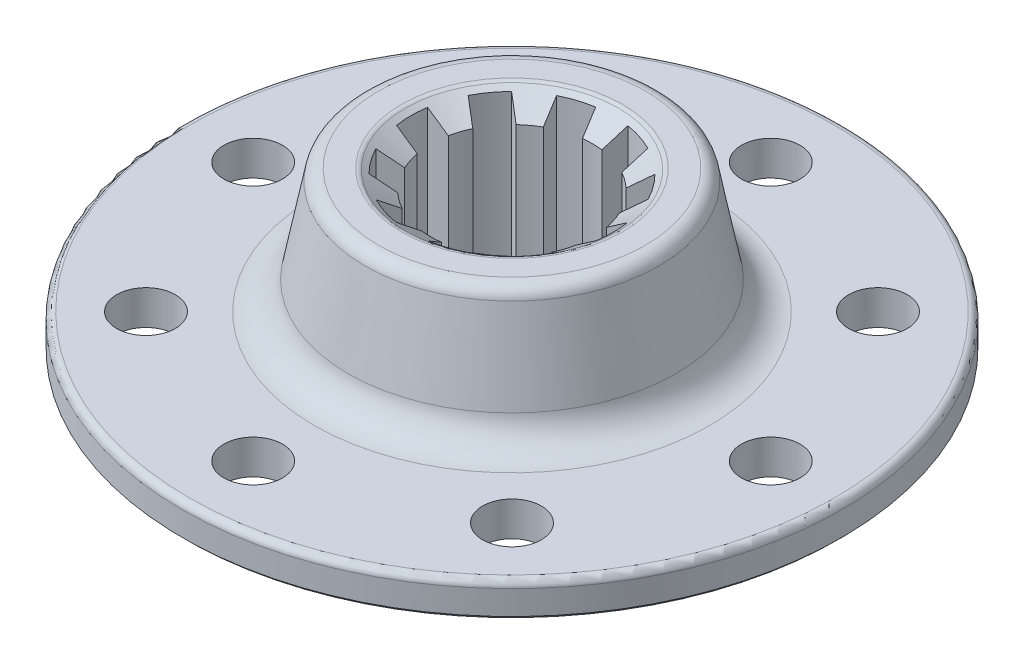
SolidWorks part; units mm, degrees
ref_plane "Plano frontal" through (0, 0, 0) normal (0, 0, 1) x (1, 0, 0)
ref_plane "Plano superior" through (0, 0, 0) normal (0, 1, 0) x (1, 0, 0)
ref_plane "Plano direito" through (0, 0, 0) normal (1, 0, 0) x (0, 0, -1)
sketch "Esboço1" plane through (0, 0, 0) normal (0, 0, 1) x (1, 0, 0)
  line L0 (0, -45.6966) -> (0, 49.4495) construction
  line L1 (11.7, 16.6829) -> (11.7, -10.8171)
  line L2 (11.7, -10.8171) -> (19.25, -10.8171)
  line L3 (19.25, -10.8171) -> (22.25, -7.8171)
  line L4 (22.25, -7.8171) -> (25.9, -7.8171)
  line L5 (27.5, -6.3171) -> (27, -5.8171)
  line L6 (27, -5.8171) -> (25.9, -5.8171)
  line L7 (27.5, -6.3171) -> (47.75, -6.3171)
  line L8 (47.75, -6.3171) -> (47.75, -1.3171)
  line L9 (21, 16.6829) -> (24.4988, -1.3171)
  line L10 (24.4988, -1.3171) -> (47.75, -1.3171)
  line L11 (21, 16.6829) -> (11.7, 16.6829)
  line L12 (25.9, -5.8171) -> (25.9, -7.8171)
  dimension "D1" = 11.7
  dimension "D2" = 21
  dimension "D3" = 11
  dimension "D4" = 3
  dimension "D5" = 19.25
  dimension "D6" = 22.25
  dimension "D7" = 25.9
  dimension "D8" = 27.5
  dimension "D9" = 0.5
  dimension "D10" = 47.75
  dimension "D11" = 4.5
  dimension "D12" = 5
  dimension "D13" = 18
revolve "Revolução1" add sketch "Esboço1" angle 360 about L0
fillet "Filete1" radius 5 1 edges at (0, -1.3171, -24.4988)
chamfer "Chanfro1" distance 4 angle 35 1 edges at (0, 16.6829, -11.7)
chamfer "Chanfro2" distance 3.5 angle 35 1 edges at (0, -10.8171, -11.7)
fillet "Filete2" radius 2 1 edges at (0, 16.6829, -21)
sketch "Esboço2" plane through (0, 16.6829, 0) normal (0, 1, 0) x (1, 0, 0)
  line L0 (-14.65, 0) -> (14.65, 0) construction
  line L1 (0, 11.7) -> (0, -11.7) construction
  line L2 (-9.6848, 2.25) -> (-9.6848, -2.25)
  line L3 (-6.5126, 7.5128) -> (-9.1577, 3.8723)
  line L4 (-14.4762, 2.25) -> (-9.6848, 2.25)
  line L5 (-14.4762, -2.25) -> (-9.6848, -2.25)
  line L6 (-10.389, 10.3292) -> (-6.5126, 7.5128)
  line L7 (-13.034, 6.6886) -> (-9.1577, 3.8723)
  line L8 (-0.8529, 9.906) -> (-5.1326, 8.5155)
  line L9 (-2.3335, 14.463) -> (-0.8529, 9.906)
  line L10 (-6.6133, 13.0724) -> (-5.1326, 8.5155)
  line L11 (5.1326, 8.5155) -> (0.8529, 9.906)
  line L12 (6.6133, 13.0724) -> (5.1326, 8.5155)
  line L13 (2.3335, 14.463) -> (0.8529, 9.906)
  line L14 (9.1577, 3.8723) -> (6.5126, 7.5128)
  line L15 (13.034, 6.6886) -> (9.1577, 3.8723)
  line L16 (10.389, 10.3292) -> (6.5126, 7.5128)
  line L17 (9.6848, -2.25) -> (9.6848, 2.25)
  line L18 (14.4762, -2.25) -> (9.6848, -2.25)
  line L19 (14.4762, 2.25) -> (9.6848, 2.25)
  line L20 (6.5126, -7.5128) -> (9.1577, -3.8723)
  line L21 (10.389, -10.3292) -> (6.5126, -7.5128)
  line L22 (13.034, -6.6886) -> (9.1577, -3.8723)
  line L23 (0.8529, -9.906) -> (5.1326, -8.5155)
  line L24 (2.3335, -14.463) -> (0.8529, -9.906)
  line L25 (6.6133, -13.0724) -> (5.1326, -8.5155)
  line L26 (-5.1326, -8.5155) -> (-0.8529, -9.906)
  line L27 (-6.6133, -13.0724) -> (-5.1326, -8.5155)
  line L28 (-2.3335, -14.463) -> (-0.8529, -9.906)
  line L29 (-9.1577, -3.8723) -> (-6.5126, -7.5128)
  line L30 (-13.034, -6.6886) -> (-9.1577, -3.8723)
  line L31 (-10.389, -10.3292) -> (-6.5126, -7.5128)
  circle A0 centre (0, 0) radius 11.7 construction
  arc A1 (-10.389, 10.3292) -> (-13.034, 6.6886) centre (0, 0) ccw
  arc A2 (-2.3335, 14.463) -> (-6.6133, 13.0724) centre (0, 0) ccw
  arc A3 (-14.4762, 2.25) -> (-14.4762, -2.25) centre (0, 0) ccw
  arc A4 (6.6133, 13.0724) -> (2.3335, 14.463) centre (0, 0) ccw
  arc A5 (13.034, 6.6886) -> (10.389, 10.3292) centre (0, 0) ccw
  arc A6 (14.4762, -2.25) -> (14.4762, 2.25) centre (0, 0) ccw
  arc A7 (10.389, -10.3292) -> (13.034, -6.6886) centre (0, 0) ccw
  arc A8 (2.3335, -14.463) -> (6.6133, -13.0724) centre (0, 0) ccw
  arc A9 (-6.6133, -13.0724) -> (-2.3335, -14.463) centre (0, 0) ccw
  arc A10 (-13.034, -6.6886) -> (-10.389, -10.3292) centre (0, 0) ccw
  dimension "D1" = 10
extrude "Corte-extrusão1" cut sketch "Esboço2" against normal through all
fillet "Filete3" radius 1 1 edges at (0, 16.6829, 15.7)
fillet "Filete4" radius 1 1 edges at (0, -1.3171, -47.75)
fillet "Filete5" radius 0.5 2 edges at (0, -5.8171, -27) (0, -5.8171, -25.9)
fillet "Filete6" radius 6 1 edges at (0, -7.8171, -22.25)
fillet "Filete7" radius 5 1 edges at (0, -10.8171, -19.25)
chamfer "Chanfro3" distance 0.5 angle 45 1 edges at (0, -6.3171, -47.75)
sketch "Esboço3" plane through (0, -6.3171, 0) normal (0, -1, 0) x (1, 0, 0)
  line L0 (-47.75, 0) -> (47.75, 0) construction
  circle A0 centre (0, 0) radius 47.75 construction
  circle A1 centre (0, 0) radius 37.5 construction
  circle A2 centre (-37.5, 0) radius 4.25
  circle A3 centre (-26.5165, 26.5165) radius 4.25
  circle A4 centre (0, 37.5) radius 4.25
  circle A5 centre (26.5165, 26.5165) radius 4.25
  circle A6 centre (37.5, 0) radius 4.25
  circle A7 centre (26.5165, -26.5165) radius 4.25
  circle A8 centre (0, -37.5) radius 4.25
  circle A9 centre (-26.5165, -26.5165) radius 4.25
  dimension "D1" = 75
  dimension "D2" = 8.5
  dimension "D3" = 8
extrude "Corte-extrusão2" cut sketch "Esboço3" against normal blind 10
